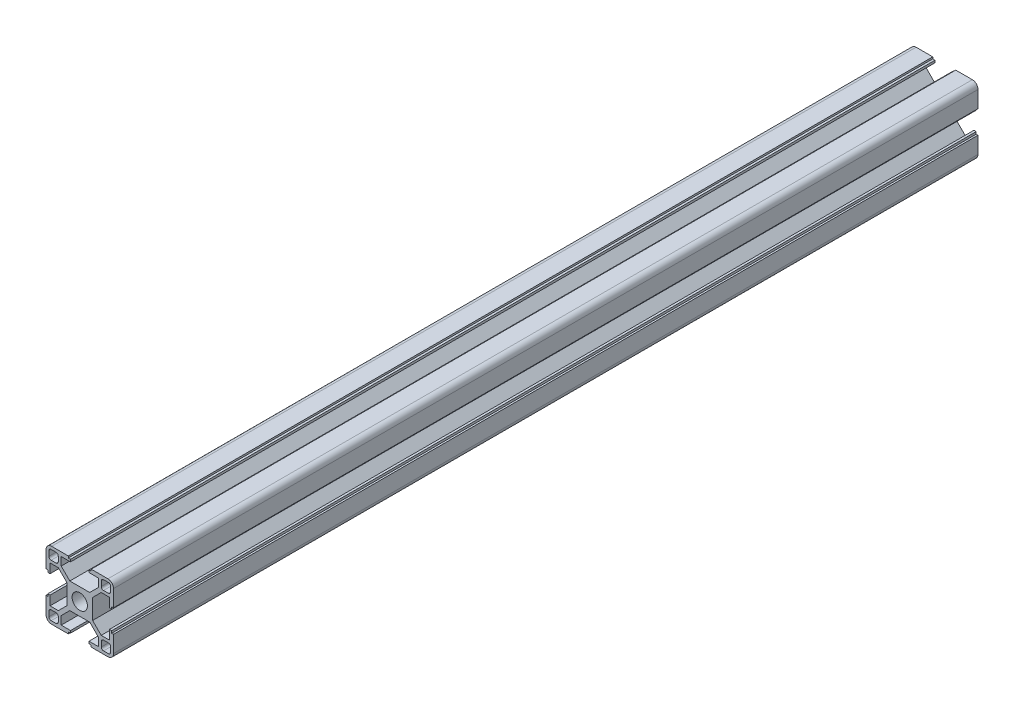
SolidWorks part; units mm, degrees
material "6061-T6 (SS)"
ref_plane "前视基准面" through (0, 0, 0) normal (0, 0, 1) x (1, 0, 0)
ref_plane "上视基准面" through (0, 0, 0) normal (0, 1, 0) x (1, 0, 0)
ref_plane "右视基准面" through (0, 0, 0) normal (1, 0, 0) x (0, 0, -1)
sketch "Sketch1" plane through (0, 0, 0) normal (0, 0, 1) x (1, 0, 0)
  line L0 (-5.1, 15) -> (-5.1, 14.2)
  line L1 (-12.5, -15) -> (12.5, -15)
  line L2 (-15, -12.5) -> (-15, 12.5)
  line L3 (-12.5, 15) -> (12.5, 15)
  line L4 (15, -12.5) -> (15, 12.5)
  line L5 (-15, -15) -> (15, 15) construction
  line L6 (-15, 15) -> (15, -15) construction
  line L7 (-5.1, 14.2) -> (-4.1, 14.2)
  line L8 (-4.1, 14.2) -> (-4.1, 13.2)
  line L9 (-4.1, 13.2) -> (-8.25, 13.2)
  line L10 (-8.25, 13.2) -> (-8.25, 9.5228)
  line L11 (-8.25, 9.5228) -> (-4.4272, 5.7)
  line L12 (-4.4272, 5.7) -> (4.4272, 5.7)
  line L13 (-5.1, 15) -> (5.1, 15)
  line L14 (0, 15) -> (0, 5.7) construction
  line L15 (8.25, 9.5228) -> (4.4272, 5.7)
  line L16 (8.25, 13.2) -> (8.25, 9.5228)
  line L17 (4.1, 13.2) -> (8.25, 13.2)
  line L18 (4.1, 14.2) -> (4.1, 13.2)
  line L19 (5.1, 14.2) -> (4.1, 14.2)
  line L20 (5.1, 15) -> (5.1, 14.2)
  line L21 (15, 5.1) -> (14.2, 5.1)
  line L22 (14.2, 5.1) -> (14.2, 4.1)
  line L23 (14.2, 4.1) -> (13.2, 4.1)
  line L24 (13.2, 4.1) -> (13.2, 8.25)
  line L25 (13.2, 8.25) -> (9.5228, 8.25)
  line L26 (9.5228, 8.25) -> (5.7, 4.4272)
  line L27 (5.7, 4.4272) -> (5.7, -4.4272)
  line L28 (15, 5.1) -> (15, -5.1)
  line L29 (9.5228, -8.25) -> (5.7, -4.4272)
  line L30 (13.2, -8.25) -> (9.5228, -8.25)
  line L31 (13.2, -4.1) -> (13.2, -8.25)
  line L32 (14.2, -4.1) -> (13.2, -4.1)
  line L33 (14.2, -5.1) -> (14.2, -4.1)
  line L34 (15, -5.1) -> (14.2, -5.1)
  line L35 (15, 0) -> (5.7, 0) construction
  line L36 (5.1, -15) -> (5.1, -14.2)
  line L37 (5.1, -14.2) -> (4.1, -14.2)
  line L38 (4.1, -14.2) -> (4.1, -13.2)
  line L39 (4.1, -13.2) -> (8.25, -13.2)
  line L40 (8.25, -13.2) -> (8.25, -9.5228)
  line L41 (8.25, -9.5228) -> (4.4272, -5.7)
  line L42 (4.4272, -5.7) -> (-4.4272, -5.7)
  line L43 (5.1, -15) -> (-5.1, -15)
  line L44 (-8.25, -9.5228) -> (-4.4272, -5.7)
  line L45 (-8.25, -13.2) -> (-8.25, -9.5228)
  line L46 (-4.1, -13.2) -> (-8.25, -13.2)
  line L47 (-4.1, -14.2) -> (-4.1, -13.2)
  line L48 (-5.1, -14.2) -> (-4.1, -14.2)
  line L49 (-5.1, -15) -> (-5.1, -14.2)
  line L50 (0, -15) -> (0, -5.7) construction
  line L51 (-15, -5.1) -> (-14.2, -5.1)
  line L52 (-14.2, -5.1) -> (-14.2, -4.1)
  line L53 (-14.2, -4.1) -> (-13.2, -4.1)
  line L54 (-13.2, -4.1) -> (-13.2, -8.25)
  line L55 (-13.2, -8.25) -> (-9.5228, -8.25)
  line L56 (-9.5228, -8.25) -> (-5.7, -4.4272)
  line L57 (-5.7, -4.4272) -> (-5.7, 4.4272)
  line L58 (-15, -5.1) -> (-15, 5.1)
  line L59 (-9.5228, 8.25) -> (-5.7, 4.4272)
  line L60 (-13.2, 8.25) -> (-9.5228, 8.25)
  line L61 (-13.2, 4.1) -> (-13.2, 8.25)
  line L62 (-14.2, 4.1) -> (-13.2, 4.1)
  line L63 (-14.2, 5.1) -> (-14.2, 4.1)
  line L64 (-15, 5.1) -> (-14.2, 5.1)
  line L65 (-15, 0) -> (-5.7, 0) construction
  line L66 (0, 0) -> (0, 5.7) construction
  circle A0 centre (0, 0) radius 3.4
  arc A1 (-12.5, -15) -> (-15, -12.5) centre (-12.5, -12.5) cw
  arc A2 (12.5, -15) -> (15, -12.5) centre (12.5, -12.5) ccw
  arc A3 (12.5, 15) -> (15, 12.5) centre (12.5, 12.5) cw
  arc A4 (-15, 12.5) -> (-12.5, 15) centre (-12.5, 12.5) cw
  point P0 (0, 0)
  dimension "D3" = 6.8
  dimension "D12" = 2.5
  dimension "D1" = 30
  dimension "D2" = 30
  dimension "D4" = 16.5
  dimension "D5" = 8.2
  dimension "D6" = 10.2
  dimension "D7" = 7.5
  dimension "D9" = 1.8
  dimension "D10" = 1.8
  dimension "D11" = 0.8
  dimension "D8" = 4
extrude "Extrude1" add sketch "Sketch1" along normal blind 384 contours A4 L2 L64 L63 L62 L61 L60 L59 L57 L56 L55 L54 L53 L52 L51 A1 L1 L49 L48 L47 L46 L45 L44 L42 L41 L40 L39 L38 L37 L36 A2 L4 L34 L33 L32 L31 L30 L29 L27 L26 L25 L24 L23 L22 L21 A3 L3 L20
sketch "Sketch2" plane through (0, 0, 384) normal (0, 0, 1) x (1, 0, 0)
  line L0 (13.7, 12.7) -> (13.7, 10.55)
  line L1 (-12.7, 13.7) -> (-10.55, 13.7)
  line L2 (-13.7, 12.7) -> (-13.7, 10.55)
  line L3 (-12.7, 9.55) -> (-10.55, 9.55)
  line L4 (-9.55, 12.7) -> (-9.55, 10.55)
  line L5 (-13.7, 13.7) -> (-9.55, 9.55) construction
  line L6 (-13.7, 9.55) -> (-9.55, 13.7) construction
  line L7 (12.7, 13.7) -> (10.55, 13.7)
  line L8 (9.55, 12.7) -> (9.55, 10.55)
  line L9 (12.7, 9.55) -> (10.55, 9.55)
  line L10 (12.7, -13.7) -> (10.55, -13.7)
  line L11 (13.7, -12.7) -> (13.7, -10.55)
  line L12 (12.7, -9.55) -> (10.55, -9.55)
  line L13 (9.55, -12.7) -> (9.55, -10.55)
  line L14 (-13.7, -12.7) -> (-13.7, -10.55)
  line L15 (-12.7, -13.7) -> (-10.55, -13.7)
  line L16 (-9.55, -12.7) -> (-9.55, -10.55)
  line L17 (-12.7, -9.55) -> (-10.55, -9.55)
  line L18 (0, 0) -> (-9.55, 9.55) construction
  line L19 (-12.5, 15) -> (-5.1, 15) construction
  line L20 (-15, 5.1) -> (-15, 12.5) construction
  line L21 (-13.2, 8.25) -> (-9.5228, 8.25) construction
  line L22 (-8.25, 13.2) -> (-8.25, 9.5228) construction
  arc A0 (-13.7, -12.7) -> (-12.7, -13.7) centre (-12.7, -12.7) ccw
  arc A1 (-10.55, -13.7) -> (-9.55, -12.7) centre (-10.55, -12.7) ccw
  arc A2 (-9.55, -10.55) -> (-10.55, -9.55) centre (-10.55, -10.55) ccw
  arc A3 (-13.7, -10.55) -> (-12.7, -9.55) centre (-12.7, -10.55) cw
  arc A4 (13.7, -10.55) -> (12.7, -9.55) centre (12.7, -10.55) ccw
  arc A5 (12.7, -13.7) -> (13.7, -12.7) centre (12.7, -12.7) ccw
  arc A6 (10.55, -13.7) -> (9.55, -12.7) centre (10.55, -12.7) cw
  arc A7 (10.55, -9.55) -> (9.55, -10.55) centre (10.55, -10.55) ccw
  arc A8 (13.7, 12.7) -> (12.7, 13.7) centre (12.7, 12.7) ccw
  arc A9 (13.7, 10.55) -> (12.7, 9.55) centre (12.7, 10.55) cw
  arc A10 (9.55, 10.55) -> (10.55, 9.55) centre (10.55, 10.55) ccw
  arc A11 (10.55, 13.7) -> (9.55, 12.7) centre (10.55, 12.7) ccw
  arc A12 (-10.55, 13.7) -> (-9.55, 12.7) centre (-10.55, 12.7) cw
  arc A13 (-10.55, 9.55) -> (-9.55, 10.55) centre (-10.55, 10.55) ccw
  arc A14 (-13.7, 10.55) -> (-12.7, 9.55) centre (-12.7, 10.55) ccw
  arc A15 (-12.7, 13.7) -> (-13.7, 12.7) centre (-12.7, 12.7) ccw
  point P0 (-11.625, 11.625)
  dimension "D2" = 1
  dimension "D3" = 1.3
  dimension "D4" = 1.3
  dimension "D5" = 1.3
  dimension "D6" = 1.3
  dimension "D1" = 4
extrude "Extrude2" cut sketch "Sketch2" against normal through all
